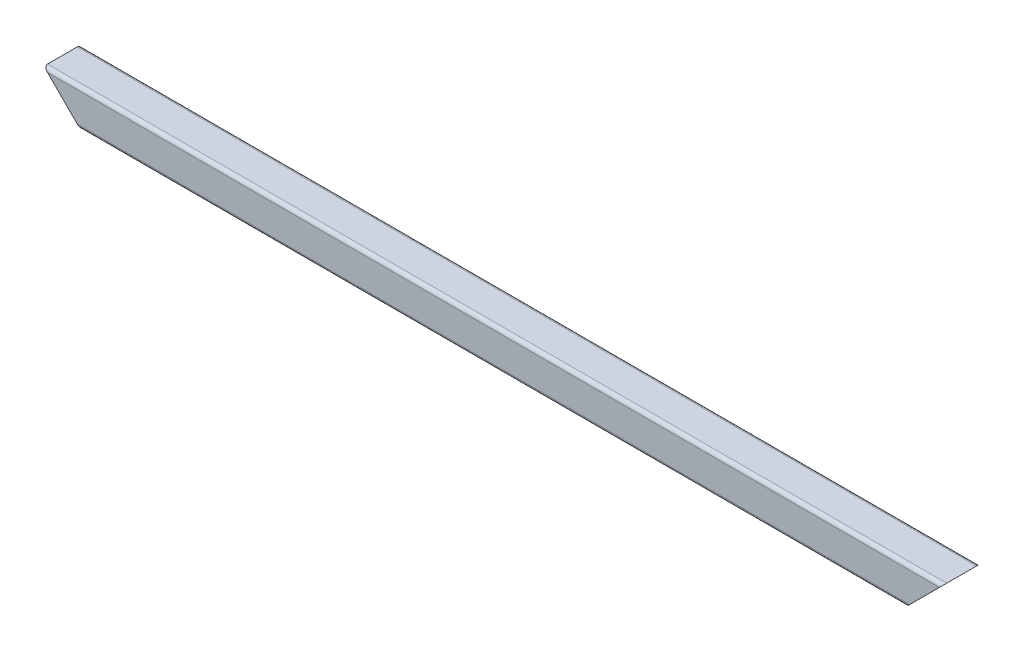
SolidWorks part; units mm, degrees
ref_plane "Front Plane" through (0, 0, 0) normal (0, 0, 1) x (1, 0, 0)
ref_plane "Top Plane" through (0, 0, 0) normal (0, 1, 0) x (1, 0, 0)
ref_plane "Right Plane" through (0, 0, 0) normal (1, 0, 0) x (0, 0, -1)
sketch "Sketch3" plane through (0, 0, 0) normal (1, 0, 0) x (0, 0, -1)
  line L1 (-12.7, 12.7) -> (12.7, 12.7)
  line L2 (-12.7, 12.7) -> (-12.7, -12.7)
  line L3 (-12.7, -12.7) -> (12.7, -12.7)
  line L4 (12.7, 12.7) -> (12.7, -12.7)
  line L5 (-12.7, 12.7) -> (12.7, -12.7) construction
  line L6 (-12.7, -12.7) -> (12.7, 12.7) construction
  line L7 (-9.652, -9.652) -> (9.652, -9.652)
  line L8 (-9.652, -9.652) -> (-9.652, 9.652)
  line L9 (-9.652, 9.652) -> (9.652, 9.652)
  line L10 (9.652, -9.652) -> (9.652, 9.652)
  line L11 (-9.652, -9.652) -> (9.652, 9.652) construction
  line L12 (-9.652, 9.652) -> (9.652, -9.652) construction
  point P0 (0, 0)
  point P6 (0, 0)
  dimension "D1" = 25.4
  dimension "D2" = 19.304
  dimension "D3" = 19.304
  dimension "D4" = 25.4
extrude "Boss-Extrude1" add sketch "Sketch3" against normal blind 616.49
fillet "Fillet1" radius 2.5 4 edges at (-308.245, -12.7, -12.7) (-308.245, -12.7, 12.7) (-308.245, 12.7, -12.7) (-308.245, 12.7, 12.7)
fillet "Fillet2" radius 1 4 edges at (-308.245, -9.652, -9.652) (-308.245, 9.652, -9.652) (-308.245, 9.652, 9.652) (-308.245, -9.652, 9.652)
sketch "Sketch4" plane through (0, 0, 12.7) normal (0, 0, 1) x (1, 0, 0)
  line L0 (-616.49, 12.7) -> (-591.09, -12.7)
  line L1 (-616.49, 12.7) -> (0, 12.7) construction
  line L2 (0, -12.7) -> (-616.49, -12.7) construction
  line L3 (-591.09, -12.7) -> (-616.49, -12.7)
  line L4 (-616.49, -12.7) -> (-616.49, 12.7)
  line L5 (-616.49, 10.2) -> (-616.49, -10.2) construction
  line L6 (0, 12.7) -> (-25.4, -12.7)
  line L7 (-25.4, -12.7) -> (0, -12.7)
  line L8 (0, -12.7) -> (0, 12.7)
  dimension "D1" = 45
  dimension "D2" = 45
extrude "Cut-Extrude1" cut sketch "Sketch4" against normal through all
